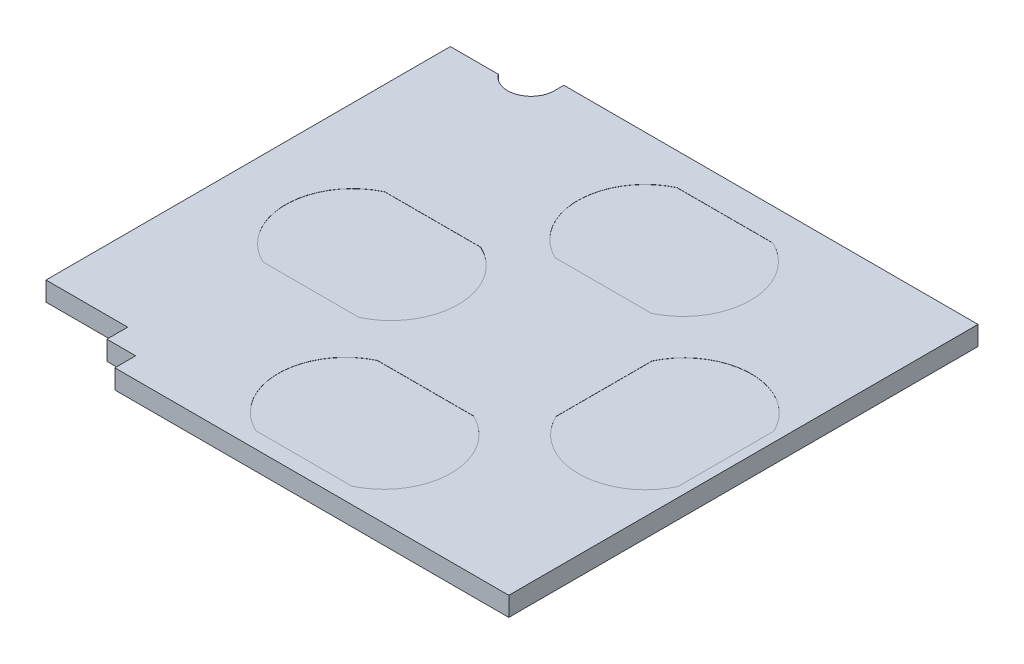
SolidWorks part; units mm, degrees
ref_plane "Plan de face" through (0, 0, 0) normal (0, 0, 1) x (1, 0, 0)
ref_plane "Plan de dessus" through (0, 0, 0) normal (0, 1, 0) x (1, 0, 0)
ref_plane "Plan de droite" through (0, 0, 0) normal (1, 0, 0) x (0, 0, -1)
sketch "Esquisse1" plane through (0, 0, 0) normal (0, 1, 0) x (1, 0, 0)
  line L0 (-15.75, 11.9) -> (-12.75, 11.9)
  line L1 (-10.2385, 13.35) -> (15.75, 13.35)
  line L2 (15.75, 13.35) -> (15.75, -15.95)
  line L3 (15.75, -15.95) -> (-8.85, -15.95)
  line L4 (-8.85, -15.95) -> (-8.85, -14.65)
  line L5 (-8.85, -14.65) -> (-10.65, -14.65)
  line L6 (-10.65, -14.65) -> (-10.65, -13.35)
  line L7 (-10.65, -13.35) -> (-15.75, -13.35)
  line L8 (-15.75, -13.35) -> (-15.75, 11.9)
  line L10 (-15.75, -13.35) -> (15.75, 13.35) construction
  arc A0 (-12.75, 11.9) -> (-10.2385, 13.35) centre (-11.5711, 12.7581) ccw
  point P0 (0, 0)
  point P4 (-11.5711, 11.3)
  point P13 (0, 0)
  dimension "D1" = 29.3
  dimension "D2" = 31.5
  dimension "D3" = 24.6
  dimension "D4" = 1.8
  dimension "D5" = 2.6
  dimension "D6" = 1.3
  dimension "D7" = 25.25
  dimension "D8" = 2.9
  dimension "D9" = 0.6
  dimension "D10" = 3
extrude "Boss.-Extru.1" add sketch "Esquisse1" along normal blind 1.2
sketch "Esquisse3" plane through (0, 1.2, 0) normal (0, 1, 0) x (1, 0, 0)
  line L0 (-10.113, 12.7581) -> (-10.113, 13.35)
  line L1 (15.75, 13.35) -> (-10.2385, 13.35) construction
  line L2 (-10.113, 13.35) -> (-10.2385, 13.35)
  arc A0 (-12.75, 11.9) -> (-10.2385, 13.35) centre (-11.5711, 12.7581) ccw construction
  arc A1 (-10.113, 12.7581) -> (-10.2385, 13.35) centre (-11.5711, 12.7581) ccw
  point P0 (-10.113, 12.7581)
extrude "Enlèv. mat.-Extru.1" cut sketch "Esquisse3" against normal blind 1.2
sketch "Esquisse4" plane through (0, 1.2, 0) normal (0, 1, 0) x (1, 0, 0)
  line L0 (-1.05, 11.35) -> (4.95, 11.35)
  line L1 (4.95, 3.75) -> (-1.05, 3.75)
  line L2 (15.75, 13.35) -> (-10.113, 13.35) construction
  line L3 (15.75, -15.95) -> (15.75, 13.35) construction
  line L4 (-1.05, -7.35) -> (4.95, -7.35)
  line L5 (4.95, -14.95) -> (-1.05, -14.95)
  line L6 (-8.85, -15.95) -> (15.75, -15.95) construction
  line L7 (-9.95, 2) -> (-3.95, 2)
  line L8 (-3.95, -5.6) -> (-9.95, -5.6)
  line L9 (1.95, 3.75) -> (1.95, -7.35) construction
  line L10 (-15.75, 11.9) -> (-15.75, -13.35) construction
  line L11 (7.55, 1.2) -> (7.55, -4.8)
  line L12 (15.15, 1.2) -> (15.15, -4.8)
  line L13 (-1.05, 11.35) -> (4.95, 3.75) construction
  line L14 (-1.05, 3.75) -> (4.95, 11.35) construction
  line L15 (-9.95, 2) -> (-3.95, -5.6) construction
  line L16 (-9.95, -5.6) -> (-3.95, 2) construction
  line L17 (7.55, 1.2) -> (15.15, -4.8) construction
  line L18 (7.55, -4.8) -> (15.15, 1.2) construction
  line L19 (4.95, -14.95) -> (-1.05, -7.35) construction
  line L20 (-1.05, -14.95) -> (4.95, -7.35) construction
  arc A0 (4.95, 11.35) -> (4.95, 3.75) centre (3.1417, 7.55) cw
  arc A1 (-1.05, 3.75) -> (-1.05, 11.35) centre (0.7583, 7.55) cw
  arc A2 (4.95, -7.35) -> (4.95, -14.95) centre (3.1417, -11.15) cw
  arc A3 (-1.05, -14.95) -> (-1.05, -7.35) centre (0.7583, -11.15) cw
  arc A4 (-3.95, 2) -> (-3.95, -5.6) centre (-5.7583, -1.8) cw
  arc A5 (-9.95, -5.6) -> (-9.95, 2) centre (-8.1417, -1.8) cw
  arc A6 (7.55, 1.2) -> (15.15, 1.2) centre (11.35, -0.6083) cw
  arc A7 (7.55, -4.8) -> (15.15, -4.8) centre (11.35, -2.9917) ccw
  point P6 (-3.45, 7.55)
  point P7 (7.35, 7.55)
  point P8 (1.95, -1.8)
  point P19 (-3.45, -11.15)
  point P20 (7.35, -11.15)
  point P24 (1.95, 3.75)
  point P25 (1.95, -7.35)
  point P32 (-12.35, -1.8)
  point P33 (-1.55, -1.8)
  point P43 (11.35, 3.6)
  point P44 (11.35, -7.2)
  point P45 (7.55, -1.8)
  point P46 (-6.95, -1.8)
  point P47 (1.95, -11.15)
  point P48 (11.35, -1.8)
  point P49 (1.95, 7.55)
  dimension "D13" = 3.4
  dimension "D1" = 10.8
  dimension "D2" = 6
  dimension "D3" = 7.6
  dimension "D4" = 2
  dimension "D5" = 8.4
  dimension "D6" = 10.8
  dimension "D7" = 6
  dimension "D8" = 7.6
  dimension "D9" = 1
  dimension "D10" = 10.8
  dimension "D11" = 6
  dimension "D12" = 7.6
  dimension "D14" = 10.8
  dimension "D15" = 7.6
  dimension "D16" = 6
  dimension "D17" = 0.6
extrude "Enlèv. mat.-Extru.2" cut sketch "Esquisse4" against normal blind 0.01
